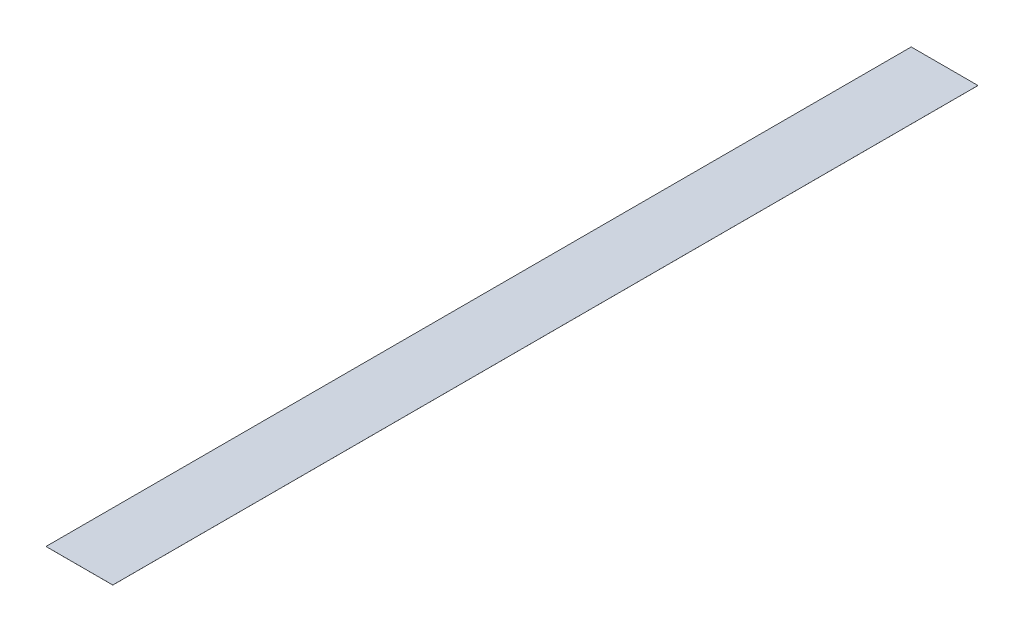
SolidWorks part; units mm, degrees
ref_plane "Plano frontal" through (0, 0, 0) normal (0, 0, 1) x (1, 0, 0)
ref_plane "Plano superior" through (0, 0, 0) normal (0, 1, 0) x (1, 0, 0)
ref_plane "Plano direito" through (0, 0, 0) normal (1, 0, 0) x (0, 0, -1)
sketch "Esboço1" plane through (0, 0, 0) normal (0, 1, 0) x (1, 0, 0)
  line L0 (-1093, 595.536) -> (-1073, 595.536)
  line L1 (0, 0) -> (18.9344, 0)
  line L2 (0, 0) -> (0, 766.8662)
  line L3 (0, 766.8662) -> (18.9344, 766.8662)
  line L4 (18.9344, 0) -> (18.9344, 766.8662)
  line L5 (-381.6968, 766.8662) -> (-362.7624, 766.8662)
  line L6 (-381.6968, 766.8662) -> (-381.6968, 345.536)
  line L7 (-381.6968, 345.536) -> (-362.7624, 345.536)
  line L8 (-362.7624, 766.8662) -> (-362.7624, 345.536)
  line L9 (-858.9344, 645.536) -> (-840, 645.536)
  line L10 (-858.9344, 645.536) -> (-858.9344, 345.536)
  line L11 (-858.9344, 345.536) -> (-840, 345.536)
  line L12 (-840, 645.536) -> (-840, 345.536)
  line L13 (-853.5858, 925.2213) -> (-1253.5858, 925.2213)
  line L14 (-853.5858, 925.2213) -> (-853.5858, 945.2213)
  line L15 (-853.5858, 945.2213) -> (-1253.5858, 945.2213)
  line L16 (-1253.5858, 925.2213) -> (-1253.5858, 945.2213)
  line L17 (-1093, 595.536) -> (-1093, 195.536)
  line L18 (-1093, 195.536) -> (-1073, 195.536)
  line L19 (-1073, 595.536) -> (-1073, 195.536)
  line L21 (-858.9344, 427.7897) -> (-1250.0103, 427.7897)
  line L23 (-858.9344, 407.7897) -> (-1250.0103, 407.7897)
  line L24 (-1250.0103, 427.7897) -> (-1250.0103, 407.7897)
  line L33 (-1439.6613, 239.7512) -> (-1560.0448, 239.7512)
  line L34 (-1439.6613, 239.7512) -> (-1439.6613, 219.7512)
  line L35 (-1439.6613, 219.7512) -> (-1560.0448, 219.7512)
  line L36 (-1560.0448, 239.7512) -> (-1560.0448, 219.7512)
  line L37 (-1627.2015, 576.144) -> (-1607.2015, 576.144)
  line L38 (-1627.2015, 576.144) -> (-1627.2015, 317.0654)
  line L39 (-1627.2015, 317.0654) -> (-1607.2015, 317.0654)
  line L40 (-1607.2015, 576.144) -> (-1607.2015, 317.0654)
  line L41 (-1627.2015, 769.6927) -> (-1607.2015, 769.6927)
  line L42 (-1627.2015, 769.6927) -> (-1627.2015, 1019.6927)
  line L43 (-1627.2015, 1019.6927) -> (-1607.2015, 1019.6927)
  line L44 (-1607.2015, 769.6927) -> (-1607.2015, 1019.6927)
  line L45 (-1829.7091, 664.7529) -> (-1809.7091, 664.7529)
  line L46 (-1829.7091, 664.7529) -> (-1829.7091, 405.6744)
  line L47 (-1829.7091, 405.6744) -> (-1809.7091, 405.6744)
  line L48 (-1809.7091, 664.7529) -> (-1809.7091, 405.6744)
  arc A6 (-381.6968, 766.8662) -> (18.9344, 766.8662) centre (-181.3812, 766.8662) cw
  arc A7 (-362.7624, 766.8662) -> (0, 766.8662) centre (-181.3812, 766.8662) cw
  arc A8 (-362.7624, 345.536) -> (-858.9344, 345.536) centre (-610.8484, 345.536) cw
  arc A9 (-381.6968, 345.536) -> (-840, 345.536) centre (-610.8484, 345.536) cw
  arc A10 (-840, 645.536) -> (-803.6955, 702.0415) centre (-777.8744, 645.536) cw
  arc A11 (-803.6955, 702.0415) -> (-853.5858, 945.2213) centre (-856.6336, 817.8884) ccw
  arc A12 (-858.9344, 645.536) -> (-814.4955, 717.9247) centre (-777.7563, 645.536) cw
  arc A13 (-814.4955, 717.9247) -> (-853.5858, 925.2213) centre (-864.2122, 815.8835) ccw
  arc A14 (-1093, 595.536) -> (-1188.5366, 677.9223) centre (-1176.2913, 595.536) ccw
  arc A15 (-1188.5366, 677.9223) -> (-1354.3411, 742.8189) centre (-1214.8489, 854.9525) cw
  arc A16 (-1354.3411, 742.8189) -> (-1253.5858, 945.2213) centre (-1257.3278, 820.805) cw
  arc A17 (-1073, 595.536) -> (-1188.5366, 698.0004) centre (-1176.2038, 595.536) ccw
  arc A18 (-1188.5366, 698.0004) -> (-1341.8208, 766.8662) centre (-1207.9995, 859.705) cw
  arc A19 (-1341.8208, 766.8662) -> (-1253.5858, 925.2213) centre (-1258.876, 824.4093) cw
  arc A22 (-1368.7558, 309.7722) -> (-1439.6613, 219.7512) centre (-1474.849, 320.402) cw
  arc A23 (-1388.5562, 309.7722) -> (-1439.6613, 239.7512) centre (-1477.6183, 321.1143) cw
  arc A24 (-1388.5562, 309.7722) -> (-1250.0103, 427.7897) centre (-1254.4723, 292.6965) cw
  arc A25 (-1607.2015, 317.0654) -> (-1560.0448, 239.7512) centre (-1520.2441, 317.0654) ccw
  arc A26 (-1627.2015, 317.0654) -> (-1560.0448, 219.7512) centre (-1523.1159, 317.0654) ccw
  arc A27 (-1368.7558, 309.7722) -> (-1250.0103, 407.7897) centre (-1259.9289, 298.8686) cw
extrude "Ressalto-extrusão17" add sketch "Esboço1" along normal blind 0.01 contours L48 L47 L46 L45
